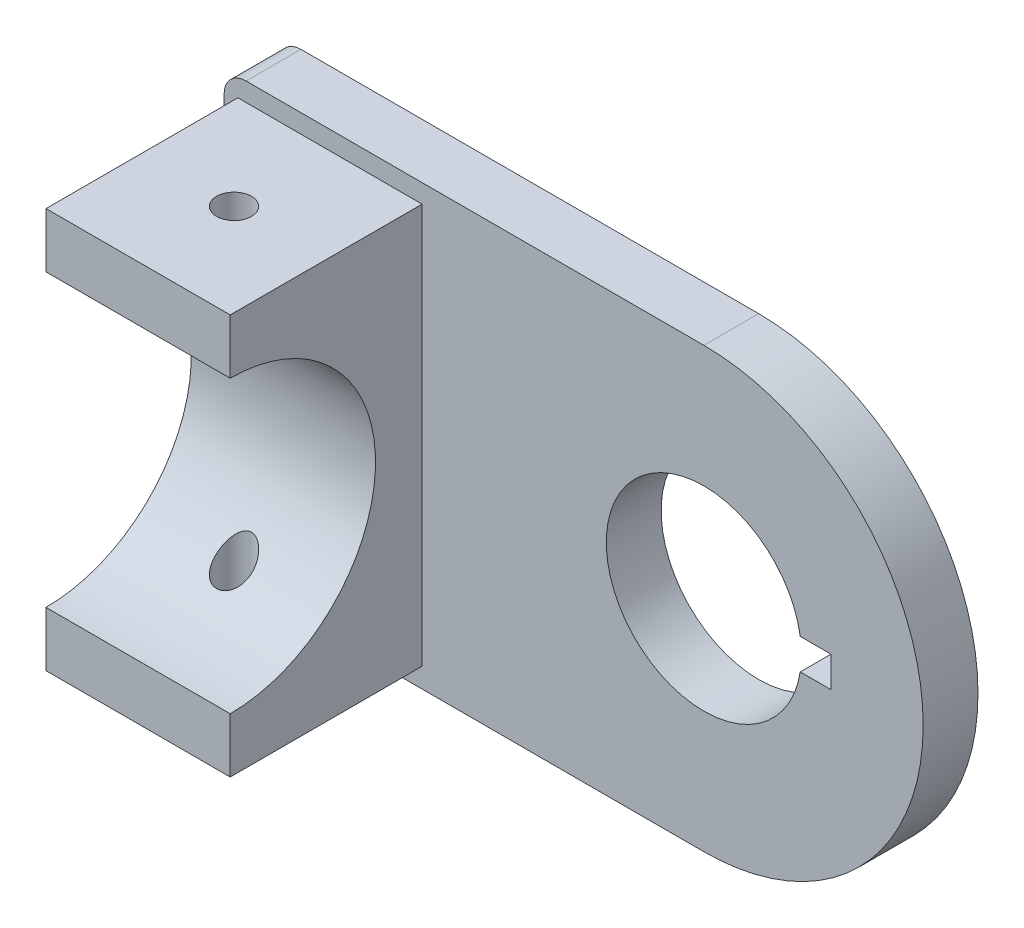
SolidWorks part; units mm, degrees
material "PET"
ref_plane "Front Plane" through (0, 0, 0) normal (0, 0, 1) x (1, 0, 0)
ref_plane "Top Plane" through (0, 0, 0) normal (0, 1, 0) x (1, 0, 0)
ref_plane "Right Plane" through (0, 0, 0) normal (1, 0, 0) x (0, 0, -1)
sketch "Sketch1" plane through (0, 0, 0) normal (0, 0, 1) x (1, 0, 0)
  line L0 (66.7248, 27.178) -> (70.2808, 27.178)
  line L1 (2.54, 0) -> (55.5625, 0)
  line L2 (0, 2.54) -> (0, 48.26)
  line L3 (2.54, 50.8) -> (55.5625, 50.8)
  line L5 (70.2808, 27.178) -> (70.2808, 23.622)
  line L6 (70.2808, 23.622) -> (66.7248, 23.622)
  line L7 (55.5625, 25.4) -> (73.7816, 25.4) construction
  arc A0 (55.5625, 0) -> (55.5625, 50.8) centre (55.5625, 25.4) ccw
  arc A1 (66.7248, 27.178) -> (66.7248, 23.622) centre (55.5625, 25.4) ccw
  arc A2 (2.54, 0) -> (0, 2.54) centre (2.54, 2.54) cw
  arc A3 (2.54, 50.8) -> (0, 48.26) centre (2.54, 48.26) ccw
  point P9 (64.6721, 25.4)
  point P14 (0, 0)
  point P17 (0, 50.8)
  dimension "D3" = 25.4
  dimension "D4" = 25.4
  dimension "D5" = 22.606
  dimension "D9" = 2.54
  dimension "D1" = 55.5625
  dimension "D2" = 50.8
  dimension "D6" = 1.778
  dimension "D7" = 1.778
  dimension "D8" = 3.556
extrude "Boss-Extrude1" add sketch "Sketch1" along normal blind 6.35
sketch "Sketch2" plane through (0, 0, 6.35) normal (0, 0, 1) x (1, 0, 0)
  line L0 (2.54, 0) -> (55.5625, 0) construction
  line L1 (1.5875, 2.286) -> (22.9235, 2.286)
  line L2 (1.5875, 2.286) -> (1.5875, 48.641)
  line L3 (1.5875, 48.641) -> (22.9235, 48.641)
  line L4 (22.9235, 2.286) -> (22.9235, 48.641)
  line L6 (0, 48.26) -> (0, 2.54) construction
  dimension "D1" = 21.336
  dimension "D2" = 46.355
  dimension "D3" = 2.286
  dimension "D4" = 1.5875
extrude "Boss-Extrude2" add sketch "Sketch2" along normal blind 22.225
sketch "Sketch3" plane through (1.5875, 0, 0) normal (-1, 0, 0) x (0, 0, 1)
  line L2 (28.575, 48.641) -> (28.575, 2.286) construction
  line L3 (28.575, 2.286) -> (6.35, 2.286) construction
  arc A1 (28.575, 8.636) -> (28.575, 42.291) centre (28.575, 25.4635) cw
  dimension "D1" = 6.35
extrude "Cut-Extrude1" cut sketch "Sketch3" against normal blind 57.531 and the other way through all flip side to cut
hole_wizard "#10-32 Tapped Hole1" positions "Sketch7" profile "Sketch6" tap size "#10-32" standard "ANSI Inch"
sketch "Sketch7" plane through (0, 48.641, 0) normal (0, 1, 0) x (1, 0, 0)
  line L0 (12.2555, -6.35) -> (12.2555, -28.575) construction
  line L1 (22.9235, -6.35) -> (1.5875, -6.35) construction
  line L2 (22.9235, -28.575) -> (1.5875, -28.575) construction
  line L4 (1.5875, -17.4625) -> (22.9235, -17.4625) construction
  line L5 (1.5875, -28.575) -> (1.5875, -6.35) construction
  line L6 (22.9235, -28.575) -> (22.9235, -6.35) construction
  point P0 (12.2555, -17.4625)
sketch "Sketch6" plane through (12.2555, 48.641, 17.4625) normal (1, 0, 0) x (0, 0, 1)
  line L0 (0, 0) -> (0, 10.5412)
  line L1 (0, 10.5412) -> (2.0193, 10.5412)
  line L2 (2.0193, 10.5412) -> (2.0193, 0)
  line L5 (2.0193, 0) -> (0, 0)
  line L11 (0, -6.35) -> (0, 107.95) construction
  dimension "Thru Tap Drill Dia." = 4.0386
  dimension "Thru Tap Drill Depth" = 10.5412
cosmetic thread "Hole Thread1" parameters "D2"=4.826
hole_wizard "#10-32 Tapped Hole2" positions "Sketch8" profile "Sketch9" tap size "#10-32" standard "ANSI Inch" end condition up to next
sketch "Sketch8" plane through (0, 2.286, 0) normal (0, -1, 0) x (-1, 0, 0)
  point P22 (-12.2555, -17.4625)
sketch "Sketch9" plane through (12.2555, 2.286, 17.4625) normal (1, 0, 0) x (0, 0, -1)
  line L0 (0, 0) -> (0, 10.5412)
  line L1 (0, 10.5412) -> (2.0193, 10.5412)
  line L2 (2.0193, 10.5412) -> (2.0193, 0)
  line L5 (2.0193, 0) -> (0, 0)
  line L11 (0, -6.35) -> (0, 107.95) construction
  dimension "Thru Tap Drill Dia." = 4.0386
  dimension "Thru Tap Drill Depth" = 10.5412
cosmetic thread "Hole Thread2" parameters "D2"=4.826
